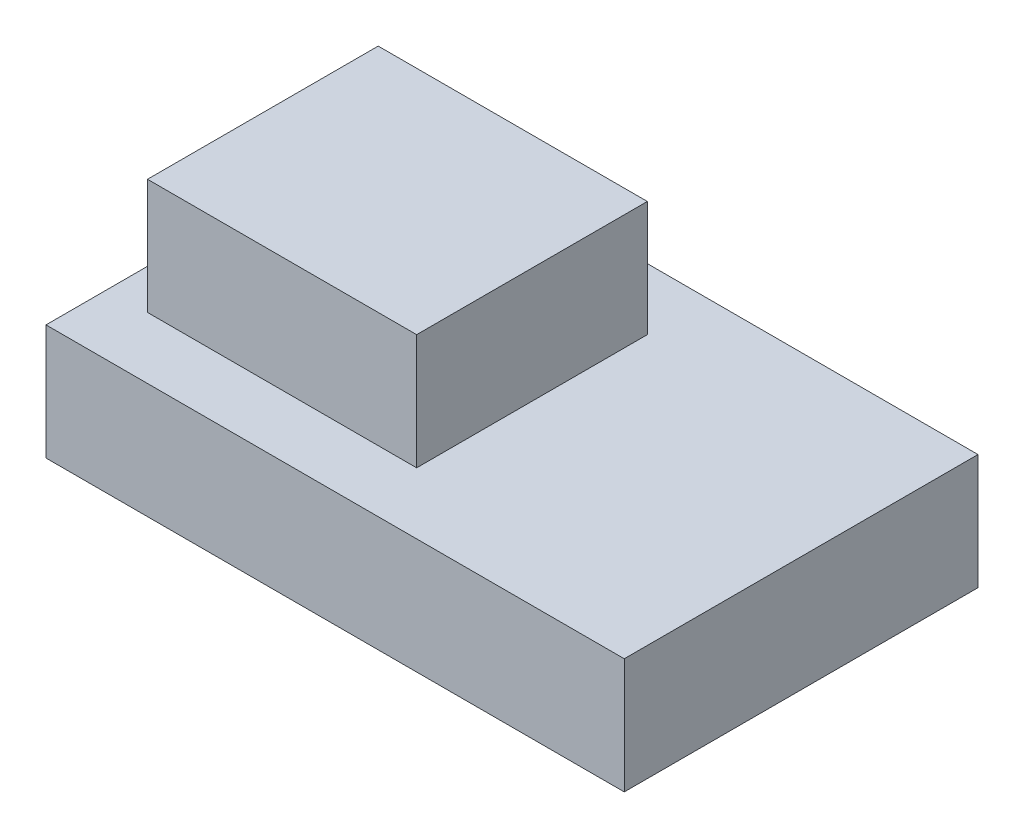
SolidWorks part; units mm, degrees
ref_plane "Front Plane" through (0, 0, 0) normal (0, 0, 1) x (1, 0, 0)
ref_plane "Top Plane" through (0, 0, 0) normal (0, 1, 0) x (1, 0, 0)
ref_plane "Right Plane" through (0, 0, 0) normal (1, 0, 0) x (0, 0, -1)
sketch "Sketch1" plane through (0, 0, 0) normal (0, 1, 0) x (1, 0, 0)
  line L1 (-47.752, -29.21) -> (47.752, -29.21)
  line L2 (-47.752, -29.21) -> (-47.752, 29.21)
  line L3 (-47.752, 29.21) -> (47.752, 29.21)
  line L4 (47.752, -29.21) -> (47.752, 29.21)
  line L5 (-47.752, -29.21) -> (47.752, 29.21) construction
  line L6 (-47.752, 29.21) -> (47.752, -29.21) construction
  point P0 (0, 0)
  dimension "D1" = 95.504
  dimension "D2" = 58.42
extrude "Boss-Extrude1" add sketch "Sketch1" along normal blind 19.05
sketch "Sketch2" plane through (0, 19.05, 0) normal (0, 1, 0) x (1, 0, 0)
  line L1 (-41.148, -19.05) -> (3.302, -19.05)
  line L2 (-41.148, -19.05) -> (-41.148, 19.05)
  line L3 (-41.148, 19.05) -> (3.302, 19.05)
  line L4 (3.302, -19.05) -> (3.302, 19.05)
  line L5 (-41.148, -19.05) -> (3.302, 19.05) construction
  line L6 (-41.148, 19.05) -> (3.302, -19.05) construction
  line L7 (47.752, -29.21) -> (47.752, 29.21) construction
  point P0 (0, 0)
  dimension "D1" = 44.45
  dimension "D2" = 38.1
  dimension "D3" = 44.45
extrude "Boss-Extrude2" add sketch "Sketch2" along normal blind 19.05
